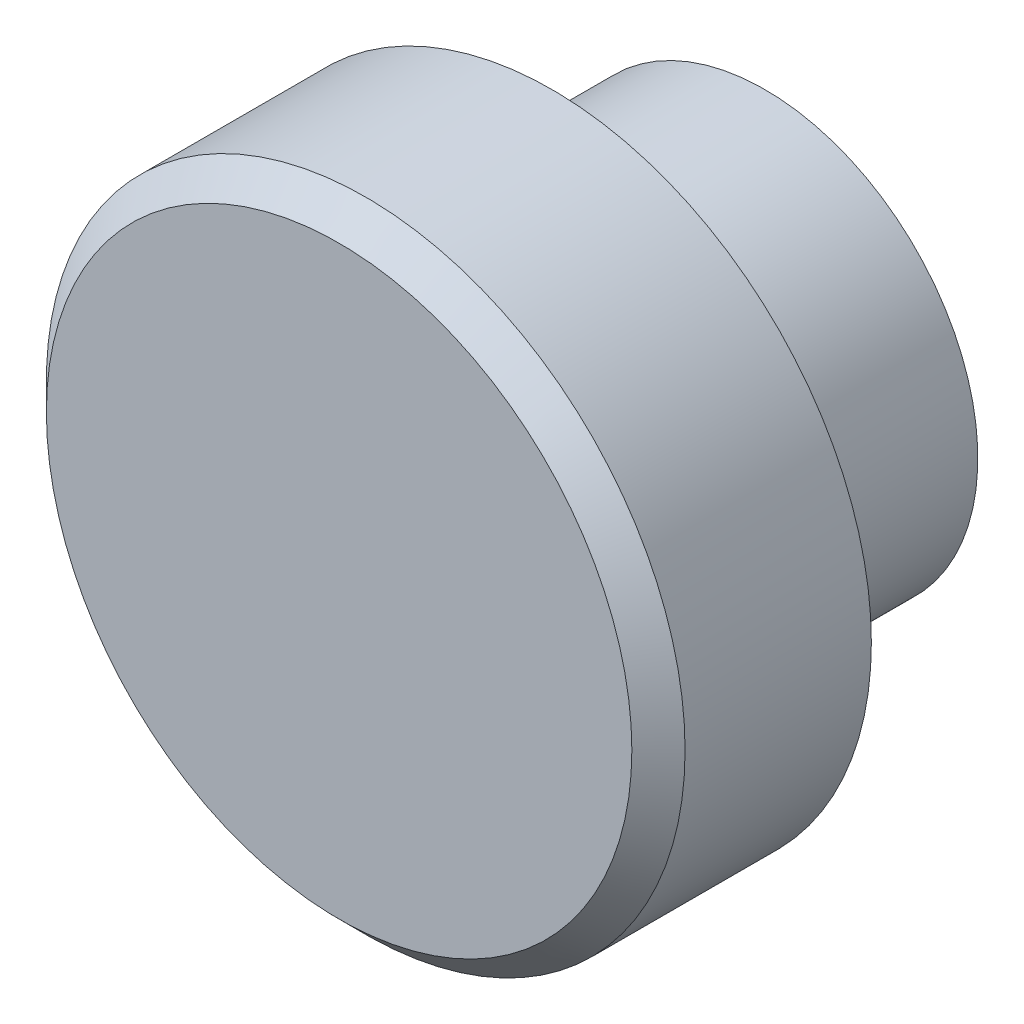
SolidWorks part; units mm, degrees
ref_plane "Front Plane" through (0, 0, 0) normal (0, 0, 1) x (1, 0, 0)
ref_plane "Top Plane" through (0, 0, 0) normal (0, 1, 0) x (1, 0, 0)
ref_plane "Right Plane" through (0, 0, 0) normal (1, 0, 0) x (0, 0, -1)
sketch "Sketch1" plane through (0, 0, 0) normal (0, 0, 1) x (1, 0, 0)
  circle A0 centre (0, 0) radius 12
  dimension "D1" = 24
extrude "Boss-Extrude1" add sketch "Sketch1" along normal blind 8
chamfer "Chamfer1" distance 1 angle 45 1 edges at (12, 0, 8)
sketch "Sketch2" plane through (0, 0, 0) normal (0, 0, -1) x (-1, 0, 0)
  circle A0 centre (0, 0) radius 8
  dimension "D1" = 16
extrude "Boss-Extrude2" add sketch "Sketch2" along normal blind 8
